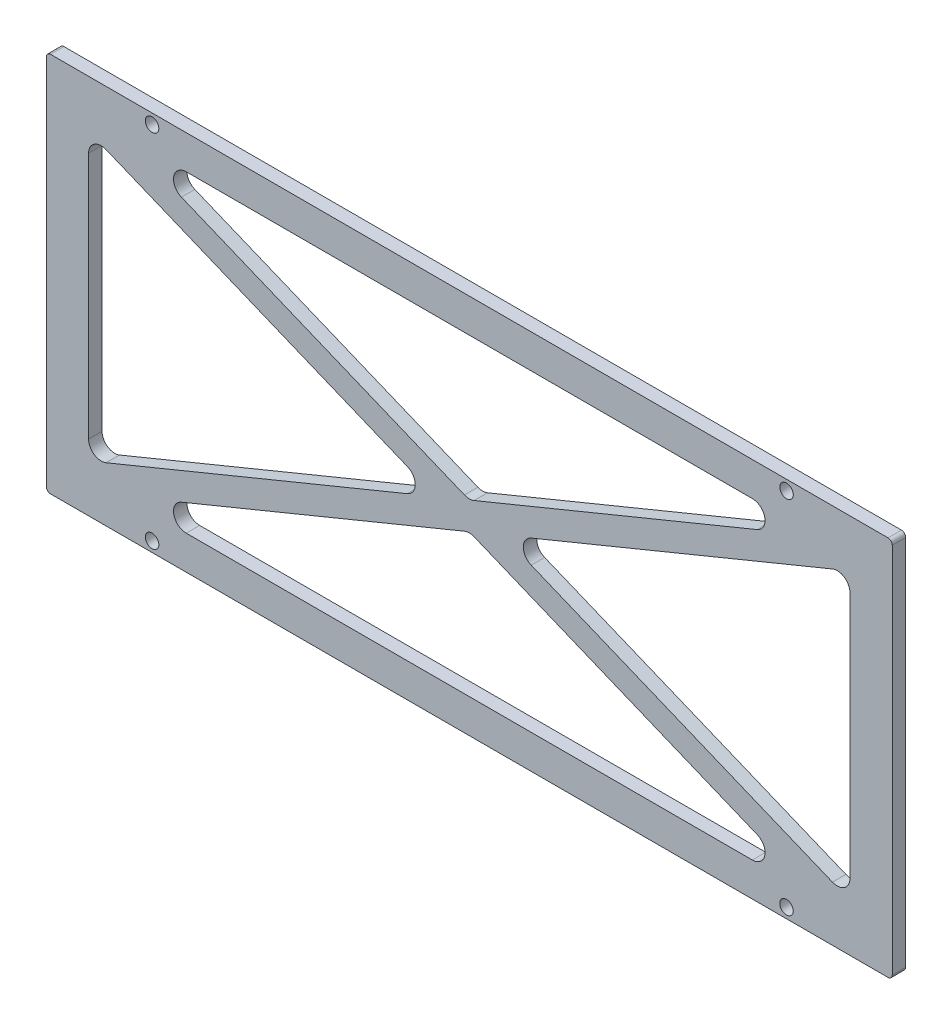
SolidWorks part; units mm, degrees
material "6061 Alloy"
ref_plane "Front Plane" through (0, 0, 0) normal (0, 0, 1) x (1, 0, 0)
ref_plane "Top Plane" through (0, 0, 0) normal (0, 1, 0) x (1, 0, 0)
ref_plane "Right Plane" through (0, 0, 0) normal (1, 0, 0) x (0, 0, -1)
sketch "Sketch1" plane through (0, 0, 0) normal (0, 0, 1) x (1, 0, 0)
  line L1 (-100, -45) -> (100, -45)
  line L2 (-100, -45) -> (-100, 45)
  line L3 (-100, 45) -> (100, 45)
  line L4 (100, -45) -> (100, 45)
  line L5 (-100, -45) -> (100, 45) construction
  line L6 (-100, 45) -> (100, -45) construction
  point P0 (0, 0)
  dimension "D1" = 90
  dimension "D2" = 200
extrude "Boss-Extrude1" add sketch "Sketch1" along normal blind 3.175
sketch "Sketch2" plane through (0, 0, 3.175) normal (0, 0, 1) x (1, 0, 0)
  line L0 (-100, -45) -> (100, -45) construction
  line L1 (-90, -37) -> (90, -37) construction
  line L2 (-90, -37) -> (-90, 37) construction
  line L3 (-90, 37) -> (90, 37) construction
  line L4 (90, -37) -> (90, 37) construction
  line L5 (-90, -37) -> (90, 37) construction
  line L6 (-90, 37) -> (90, -37) construction
  line L7 (-82.1101, 37) -> (82.1101, 37)
  line L8 (-91.1407, 34.2253) -> (88.8593, -39.7747) construction
  line L9 (-88.8593, -39.7747) -> (91.1407, 34.2253) construction
  line L10 (-88.8593, 39.7747) -> (91.1407, -34.2253) construction
  line L11 (-91.1407, -34.2253) -> (88.8593, 39.7747) construction
  line L12 (-90, 33.7564) -> (-90, -33.7564)
  line L13 (-90, -33.7564) -> (-7.8899, 0)
  line L14 (-7.8899, 0) -> (-90, 33.7564)
  line L15 (82.1101, 37) -> (0, 3.2436)
  line L16 (0, 3.2436) -> (-82.1101, 37)
  line L17 (90, 33.7564) -> (7.8899, 0)
  line L18 (7.8899, 0) -> (90, -33.7564)
  line L19 (90, -33.7564) -> (90, 33.7564)
  line L20 (-82.1101, -37) -> (0, -3.2436)
  line L21 (0, -3.2436) -> (82.1101, -37)
  line L22 (82.1101, -37) -> (-82.1101, -37)
  point P0 (0, 0)
  dimension "D1" = 8
  dimension "D2" = 3
  dimension "D3" = 180
  dimension "D4" = 3
extrude "Cut-Extrude1" cut sketch "Sketch2" against normal through all
sketch "Sketch3" plane through (0, 0, 3.175) normal (0, 0, 1) x (1, 0, 0)
  line L0 (100, 45) -> (-100, 45) construction
  line L1 (-75, -42.6187) -> (75, -42.6187) construction
  line L2 (-75, -42.6187) -> (-75, 42.6188) construction
  line L3 (-75, 42.6188) -> (75, 42.6188) construction
  line L4 (75, -42.6187) -> (75, 42.6188) construction
  line L5 (-75, -42.6187) -> (75, 42.6188) construction
  line L6 (-75, 42.6188) -> (75, -42.6187) construction
  point P0 (0, 0)
  dimension "D1" = 2.3813
  dimension "D2" = 150
hole_wizard "M3 Clearance Hole1" positions "Sketch4" profile "Sketch5" hole size "M3" standard "ANSI Metric" end condition through all
sketch "Sketch4" plane through (0, 0, 3.175) normal (0, 0, 1) x (1, 0, 0)
  point P0 (-75, 42.6188)
  point P3 (75, 42.6188)
  point P6 (75, -42.6187)
  point P9 (-75, -42.6187)
sketch "Sketch5" plane through (-75, 42.6188, 3.175) normal (1, 0, 0) x (0, -1, 0)
  line L0 (0, 0) -> (0, 3.175)
  line L1 (0, 3.175) -> (1.6, 3.175)
  line L2 (1.6, 3.175) -> (1.6, 0)
  line L5 (1.6, 0) -> (0, 0)
  line L11 (0, -6.35) -> (0, 107.95) construction
  dimension "Thru Hole Dia." = 3.2
  dimension "Thru Hole Depth" = 3.175
fillet "Fillet1" radius 3 12 edges at (-82.1101, 37, 1.5875) (82.1101, 37, 1.5875) (0, 3.2436, 1.5875) (90, -33.7564, 1.5875) (90, 33.7564, 1.5875) (7.8899, 0, 1.5875) (0, -3.2436, 1.5875) (82.1101, -37, 1.5875) (-82.1101, -37, 1.5875) (-7.8899, 0, 1.5875) (-90, 33.7564, 1.5875) (-90, -33.7564, 1.5875)
fillet "Fillet2" radius 1 4 edges at (-100, 45, 1.5875) (100, 45, 1.5875) (-100, -45, 1.5875) (100, -45, 1.5875)
